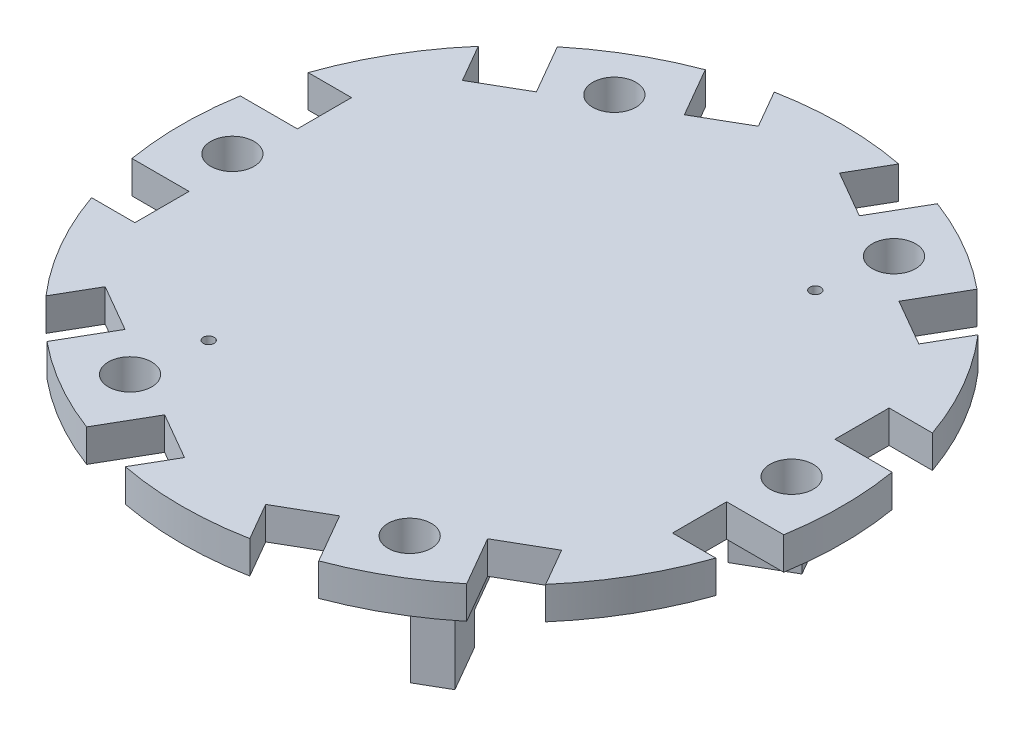
SolidWorks part; units mm, degrees
ref_plane "Alzado" through (0, 0, 0) normal (0, 0, 1) x (1, 0, 0)
ref_plane "Planta" through (0, 0, 0) normal (0, 1, 0) x (1, 0, 0)
ref_plane "Vista lateral" through (0, 0, 0) normal (1, 0, 0) x (0, 0, -1)
sketch "Croquis1" plane through (0, 0, 0) normal (0, 1, 0) x (1, 0, 0)
  circle A0 centre (0, 0) radius 30.5
extrude "Saliente-Extruir1" add sketch "Croquis1" along normal blind 3
sketch "Croquis5" plane through (0, 3, 0) normal (0, 1, 0) x (1, 0, 0)
  line L1 (28.8141, -5) -> (30.0874, -5)
  line L2 (28.8141, 5) -> (30.0874, 5)
  line L3 (-24.8141, 10) -> (-28.8141, 10)
  line L4 (24.8141, -5) -> (24.8141, -10)
  line L5 (-24.8141, -10) -> (-28.8141, -10)
  line L6 (24.8141, -5) -> (28.8141, -5)
  line L7 (24.8141, 5) -> (24.8141, 10)
  line L8 (-24.8141, 5) -> (-28.8141, 5)
  line L9 (-24.8141, 5) -> (-24.8141, 10)
  line L10 (-24.8141, -5) -> (-28.8141, -5)
  line L11 (-24.8141, -5) -> (-24.8141, -10)
  line L12 (24.8141, 5) -> (28.8141, 5)
  line L13 (24.8141, -10) -> (28.8141, -10)
  line L14 (24.8141, 10) -> (28.8141, 10)
  line L15 (-28.8141, 5) -> (-30.0874, 5)
  line L16 (-28.8141, -5) -> (-30.0874, -5)
  line L17 (18.7372, 22.4537) -> (19.3738, 23.5564)
  line L18 (-24.8141, 0) -> (-12.407, -21.4896)
  line L19 (-12.407, -21.4896) -> (12.407, -21.4896)
  line L20 (12.407, -21.4896) -> (24.8141, 0)
  line L21 (24.8141, 0) -> (12.407, 21.4896)
  line L22 (12.407, 21.4896) -> (-12.407, 21.4896)
  line L23 (-12.407, 21.4896) -> (-24.8141, 0)
  line L24 (-21.0673, -16.4896) -> (-23.0673, -19.9537)
  line L25 (-3.7468, -26.4896) -> (-5.7468, -29.9537)
  line L26 (-16.7372, -18.9896) -> (-18.7372, -22.4537)
  line L27 (-16.7372, -18.9896) -> (-21.0673, -16.4896)
  line L28 (-8.0769, -23.9896) -> (-10.0769, -27.4537)
  line L29 (-8.0769, -23.9896) -> (-3.7468, -26.4896)
  line L30 (-18.7372, -22.4537) -> (-19.3738, -23.5564)
  line L31 (-10.0769, -27.4537) -> (-10.7136, -28.5564)
  line L32 (10.0769, 27.4537) -> (10.7136, 28.5564)
  line L33 (16.7372, 18.9896) -> (21.0673, 16.4896)
  line L34 (16.7372, 18.9896) -> (18.7372, 22.4537)
  line L35 (8.0769, 23.9896) -> (3.7468, 26.4896)
  line L36 (8.0769, 23.9896) -> (10.0769, 27.4537)
  line L37 (21.0673, 16.4896) -> (23.0673, 19.9537)
  line L38 (3.7468, 26.4896) -> (5.7468, 29.9537)
  line L39 (-3.7468, 26.4896) -> (-5.7468, 29.9537)
  line L40 (-21.0673, 16.4896) -> (-23.0673, 19.9537)
  line L41 (-8.0769, 23.9896) -> (-10.0769, 27.4537)
  line L42 (-8.0769, 23.9896) -> (-3.7468, 26.4896)
  line L43 (-16.7372, 18.9896) -> (-18.7372, 22.4537)
  line L44 (-16.7372, 18.9896) -> (-21.0673, 16.4896)
  line L45 (-10.0769, 27.4537) -> (-10.7136, 28.5564)
  line L46 (-18.7372, 22.4537) -> (-19.3738, 23.5564)
  line L47 (10.0769, -27.4537) -> (10.7136, -28.5564)
  line L48 (18.7372, -22.4537) -> (19.3738, -23.5564)
  line L49 (8.0769, -23.9896) -> (3.7468, -26.4896)
  line L50 (8.0769, -23.9896) -> (10.0769, -27.4537)
  line L51 (16.7372, -18.9896) -> (21.0673, -16.4896)
  line L52 (16.7372, -18.9896) -> (18.7372, -22.4537)
  line L53 (3.7468, -26.4896) -> (5.7468, -29.9537)
  line L54 (21.0673, -16.4896) -> (23.0673, -19.9537)
  circle A0 centre (0, 0) radius 21.4896 construction
  circle A1 centre (0, 0) radius 30.5 construction
  arc A2 (-28.8141, 10) -> (-30.0874, 5) centre (0, 0) ccw
  arc A3 (-5.7468, 29.9537) -> (-10.7136, 28.5564) centre (0, 0) ccw
  arc A4 (-30.0874, -5) -> (-28.8141, -10) centre (0, 0) ccw
  arc A5 (30.0874, -5) -> (28.8141, -10) centre (0, 0) cw
  arc A6 (28.8141, 10) -> (30.0874, 5) centre (0, 0) cw
  arc A7 (-23.0673, -19.9537) -> (-19.3738, -23.5564) centre (0, 0) ccw
  arc A8 (-10.7136, -28.5564) -> (-5.7468, -29.9537) centre (0, 0) ccw
  arc A9 (-19.3738, 23.5564) -> (-23.0673, 19.9537) centre (0, 0) ccw
  arc A10 (19.3738, 23.5564) -> (23.0673, 19.9537) centre (0, 0) cw
  arc A11 (5.7468, 29.9537) -> (10.7136, 28.5564) centre (0, 0) cw
  arc A12 (10.7136, -28.5564) -> (5.7468, -29.9537) centre (0, 0) cw
  arc A13 (23.0673, -19.9537) -> (19.3738, -23.5564) centre (0, 0) cw
  circle M2 centre (0, 0) radius 30.5
extrude "Cortar-Extruir3" cut sketch "Croquis5" against normal blind 4 contours L15 L8 L9 L3 M2 | L14 L7 L12 L2 M2 | L4 L13 L1 L6 M2 | L54 L51 L52 L48 M2 | L49 L53 L47 L50 M2 | L28 L31 L25 L29 M2 | L30 L26 L27 L24 M2 | L10 L16 L5 L11 M2 | L43 L46 L40 L44 M2 | L45 L41 L42 L39 M2 | L38 L35 L36 L32 M2 | L33 L37 L17 L34 M2
sketch "Croquis7" plane through (0, 3, 0) normal (0, 1, 0) x (1, 0, 0)
  line L2 (25.8141, 0) -> (12.907, 22.3556)
  line L3 (12.907, 22.3556) -> (-12.907, 22.3556)
  line L4 (-12.907, 22.3556) -> (-25.8141, 0)
  line L5 (-25.8141, 0) -> (-12.907, -22.3556)
  line L6 (-12.907, -22.3556) -> (12.907, -22.3556)
  line L7 (12.907, -22.3556) -> (25.8141, 0)
  circle A0 centre (25.8141, 0) radius 2
  circle A4 centre (-25.8141, 0) radius 2
  circle A5 centre (0, 0) radius 22.3556 construction
  circle A6 centre (12.907, 22.3556) radius 2
  circle A7 centre (-12.907, -22.3556) radius 2
  circle A8 centre (-12.907, 22.3556) radius 2
  circle A9 centre (12.907, -22.3556) radius 2
extrude "Cortar-Extruir4" cut sketch "Croquis7" against normal blind 10 contours A8 L4 L3 | A4 L4 L5 | A4 L5 L4 | A8 L3 L4 | L2 A6 L3 | L3 A6 L2 | L7 A0 L2 | L2 A0 L7 | A7 L5 L6 | A7 L6 L5 | L6 A9 L7 | L7 A9 L6
sketch "Croquis8" plane through (0, 3, 0) normal (0, 1, 0) x (1, 0, 0)
  line L0 (0, 0) -> (12, 0)
  line L1 (12, 0) -> (12, 16)
  line L2 (0, 0) -> (-12, 0)
  line L3 (-12, 0) -> (-12, -16)
  circle A0 centre (12, 16) radius 0.5
  circle A1 centre (-12, -16) radius 0.5
extrude "Cortar-Extruir5" cut sketch "Croquis8" against normal blind 3
sketch "Croquis9" plane through (0, 3, 0) normal (0, 1, 0) x (1, 0, 0)
  line L0 (16.5705, 11.299) -> (-18.0705, -8.701)
  line L1 (-8.701, 18.0705) -> (11.299, -16.5705)
  line L2 (-10, 17.3205) -> (-8.701, 18.0705)
  line L3 (8.701, -18.0705) -> (-11.299, 16.5705)
  line L4 (-16.5705, -11.299) -> (18.0705, 8.701)
  line L5 (25.6318, 16.5306) -> (27.1318, 13.9325)
  line L6 (-10, 17.3205) -> (-11.299, 16.5705)
  line L7 (17.3205, 10) -> (16.5705, 11.299)
  line L8 (10, -17.3205) -> (8.701, -18.0705)
  line L9 (10, -17.3205) -> (11.299, -16.5705)
  line L11 (-17.3205, -10) -> (-16.5705, -11.299)
  line L12 (-17.3205, -10) -> (-18.0705, -8.701)
  line L14 (17.3205, 10) -> (18.0705, 8.701)
extrude "Saliente-Extruir2" add sketch "Croquis9" against normal blind 13 contours L12 L11 L4 L3 L0 | L3 L4 L1 L0 | L2 L6 L3 L0 L1 | L14 L7 L0 L1 L4 | L8 L9 L1 L4 L3
sketch "Croquis10" plane through (0, -10, 0) normal (0, -1, 0) x (-1, 0, 0)
  line L0 (8.701, 18.0705) -> (11.299, 16.5705)
  line L1 (8.701, 18.0705) -> (6.201, 13.7404)
  line L2 (11.299, 16.5705) -> (8.799, 12.2404)
  line L3 (6.201, 13.7404) -> (8.799, 12.2404)
  line L8 (-12.2404, 8.799) -> (-13.7404, 6.201)
  line L9 (-16.5705, 11.299) -> (-12.2404, 8.799)
  line L10 (-18.0705, 8.701) -> (-13.7404, 6.201)
  line L11 (-16.5705, 11.299) -> (-18.0705, 8.701)
  line L12 (-8.701, -18.0705) -> (-11.299, -16.5705)
  line L13 (-11.299, -16.5705) -> (-8.799, -12.2404)
  line L14 (-8.701, -18.0705) -> (-6.201, -13.7404)
  line L15 (-6.201, -13.7404) -> (-8.799, -12.2404)
  line L16 (12.2404, -8.799) -> (13.7404, -6.201)
  line L17 (18.0705, -8.701) -> (13.7404, -6.201)
  line L18 (16.5705, -11.299) -> (12.2404, -8.799)
  line L19 (16.5705, -11.299) -> (18.0705, -8.701)
extrude "Saliente-Extruir3" add sketch "Croquis10" along normal blind 3
fillet "Redondeo1" radius 1 12 edges at (4.076, 0, 10.0598) (-8.5598, 0, 6.674) (-17.3205, 0, 10) (10, 0, 17.3205) (6.674, 0, 8.5598) (10.0598, 0, -4.076) (17.3205, 0, -10) (8.5598, 0, -6.674) (-4.076, 0, -10.0598) (-10, 0, -17.3205) (-6.674, 0, -8.5598) (-10.0598, 0, 4.076)
